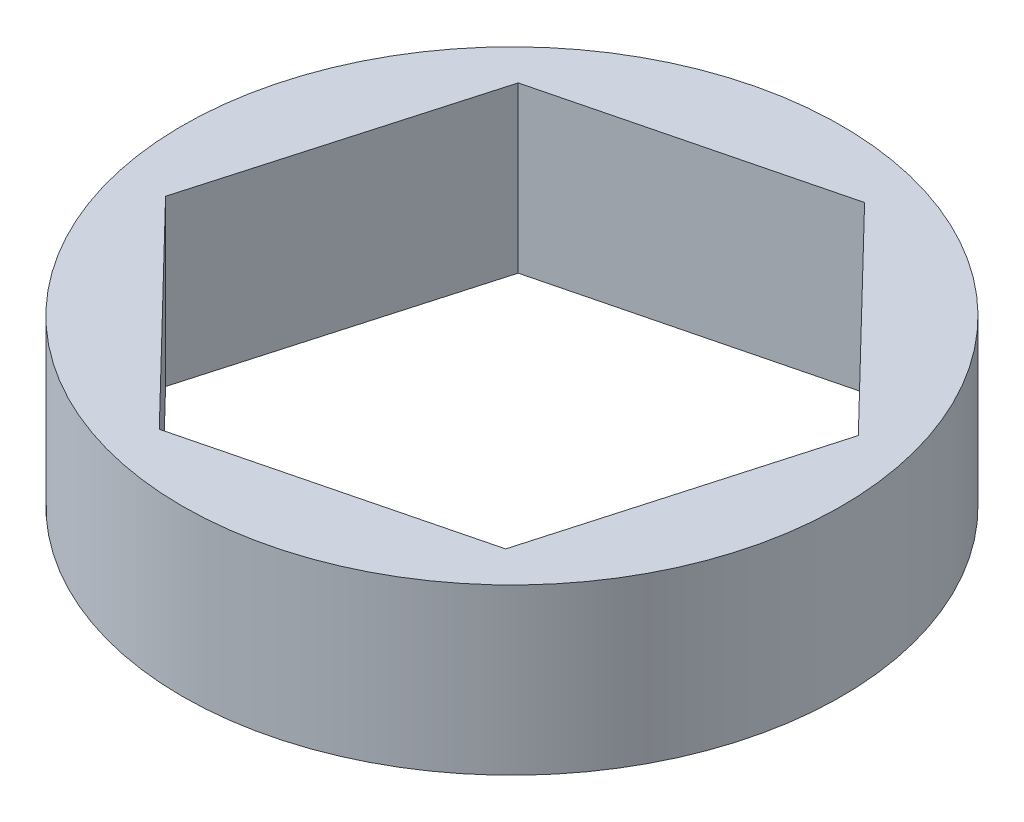
SolidWorks part; units mm, degrees
ref_plane "Front Plane" through (0, 0, 0) normal (0, 0, 1) x (1, 0, 0)
ref_plane "Top Plane" through (0, 0, 0) normal (0, 1, 0) x (1, 0, 0)
ref_plane "Right Plane" through (0, 0, 0) normal (1, 0, 0) x (0, 0, -1)
sketch "Sketch1" plane through (0, 0, 0) normal (0, 1, 0) x (1, 0, 0)
  line L1 (1.5057, 5.2891) -> (-3.8277, 3.9485)
  line L2 (-3.8277, 3.9485) -> (-5.3333, -1.3406)
  line L3 (-5.3333, -1.3406) -> (-1.5057, -5.2891)
  line L4 (-1.5057, -5.2891) -> (3.8277, -3.9485)
  line L5 (3.8277, -3.9485) -> (5.3333, 1.3406)
  line L6 (5.3333, 1.3406) -> (1.5057, 5.2891)
  circle A0 centre (0, 0) radius 4.7625 construction
  circle A1 centre (0, 0) radius 6.35
  dimension "D2" = 12.7
  dimension "D1" = 9.525
extrude "Boss-Extrude1" add sketch "Sketch1" along normal blind 3.175
